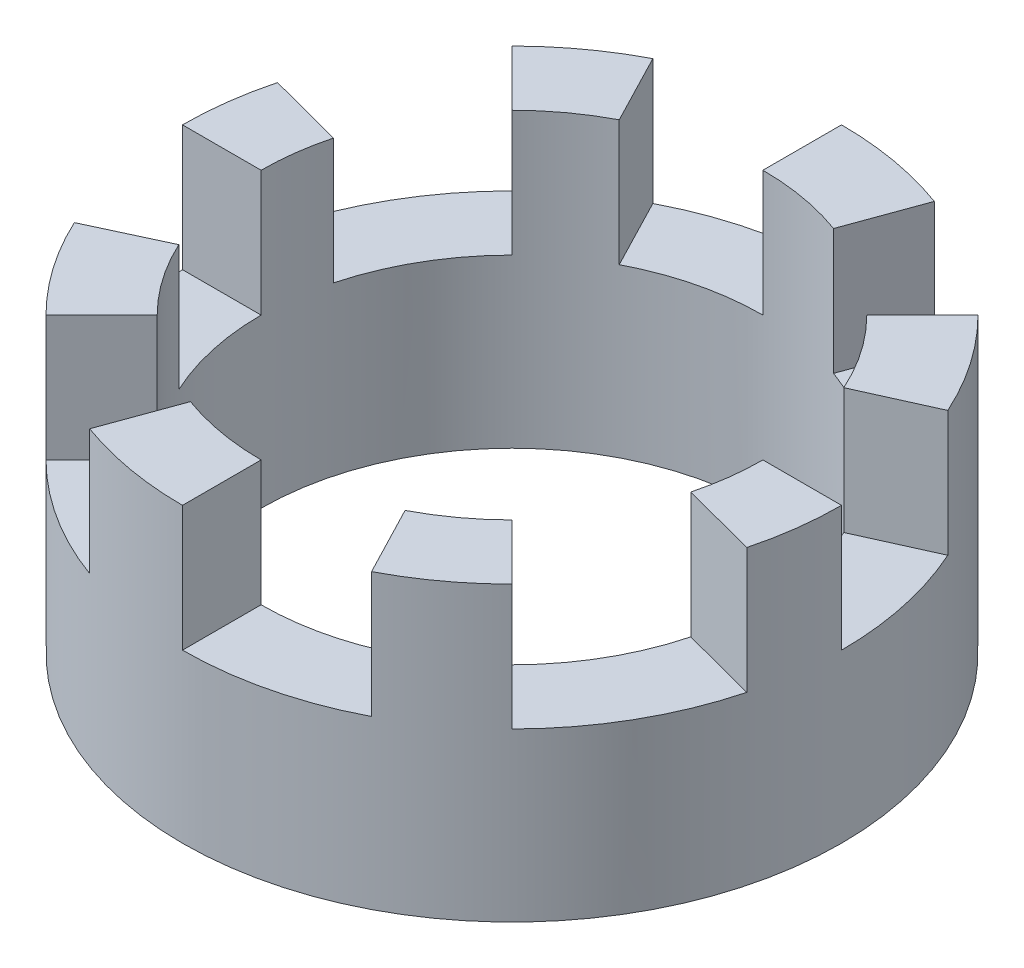
SolidWorks part; units mm, degrees
ref_plane "Front Plane" through (0, 0, 0) normal (0, 0, 1) x (1, 0, 0)
ref_plane "Top Plane" through (0, 0, 0) normal (0, 1, 0) x (1, 0, 0)
ref_plane "Right Plane" through (0, 0, 0) normal (1, 0, 0) x (0, 0, -1)
sketch "Sketch1" plane through (0, 0, 0) normal (0, 1, 0) x (1, 0, 0)
  circle A0 centre (0, 0) radius 30
  circle A1 centre (0, 0) radius 39.4
extrude "Boss-Extrude1" add sketch "Sketch1" along normal blind 20
sketch "Sketch2" plane through (0, 20, 0) normal (0, 1, 0) x (1, 0, 0)
  line L0 (-30, 0) -> (-39.4, 0) construction
  line L1 (-38.0947, 10.0575) -> (-29.0061, 7.658)
  line L2 (30, 0) -> (39.4, 0) construction
  line L3 (38.102, -10.0298) -> (29.0117, -7.6369)
  line L4 (0, 30) -> (0, 39.4) construction
  line L5 (0, -30) -> (0, -39.4) construction
  line L6 (-13.4756, -37.0239) -> (-10.2606, -28.1908)
  line L7 (13.4756, 37.0239) -> (10.2606, 28.1908)
  line L8 (-21.2132, 21.2132) -> (-27.86, 27.86)
  line L9 (-18.1365, 34.9775) -> (-13.8095, 26.6326)
  line L10 (-21.2132, 21.2132) -> (21.2132, -21.2132) construction
  line L11 (21.2132, -21.2132) -> (27.86, -27.86) construction
  line L12 (21.2132, -21.2132) -> (27.86, -27.86)
  line L13 (18.1686, -34.9608) -> (13.834, -26.6199)
  line L14 (-39.4, 0) -> (-30, 0)
  line L15 (0, -30) -> (0, -39.4)
  line L16 (30, 0) -> (39.4, 0)
  line L17 (0, 30) -> (0, 39.4)
  line L18 (-21.2132, -21.2132) -> (-27.86, -27.86)
  line L19 (-27.86, -27.86) -> (21.2132, 21.2132)
  line L20 (21.2132, 21.2132) -> (27.86, 27.86)
  line L21 (-35.7392, -16.5852) -> (-27.2126, -12.6283)
  line L22 (35.9235, 16.1822) -> (27.3529, 12.3215)
  circle A0 centre (0, 0) radius 30 construction
  circle A1 centre (0, 0) radius 39.4 construction
  arc A2 (-39.4, 0) -> (-38.0947, 10.0575) centre (0, 0) cw
  arc A3 (-29.0061, 7.658) -> (-30, 0) centre (0, 0) ccw
  arc A4 (39.4, 0) -> (38.102, -10.0298) centre (0, 0) cw
  arc A5 (30, 0) -> (29.0117, -7.6369) centre (0, 0) cw
  arc A6 (0, -39.4) -> (-13.4756, -37.0239) centre (0, 0) cw
  arc A7 (0, -30) -> (-10.2606, -28.1908) centre (0, 0) cw
  arc A8 (0, 39.4) -> (13.4756, 37.0239) centre (0, 0) cw
  arc A9 (0, 30) -> (10.2606, 28.1908) centre (0, 0) cw
  arc A10 (-30, 0) -> (-21.2132, 21.2132) centre (0, 0) cw
  arc A11 (-27.86, 27.86) -> (-18.1365, 34.9775) centre (0, 0) cw
  arc A12 (-21.2132, 21.2132) -> (-13.8095, 26.6326) centre (0, 0) cw
  arc A13 (27.86, -27.86) -> (18.1686, -34.9608) centre (0, 0) cw
  arc A14 (13.834, -26.6199) -> (21.2132, -21.2132) centre (0, 0) ccw
  arc A15 (-27.86, -27.86) -> (-35.7392, -16.5852) centre (0, 0) cw
  arc A16 (-27.2126, -12.6283) -> (-21.2132, -21.2132) centre (0, 0) ccw
  arc A17 (27.86, 27.86) -> (35.9235, 16.1822) centre (0, 0) cw
  arc A18 (27.3529, 12.3215) -> (21.2132, 21.2132) centre (0, 0) ccw
  circle M5 centre (0, 0) radius 39.4
  circle M6 centre (0, 0) radius 30
extrude "Boss-Extrude2" add sketch "Sketch2" along normal blind 15 contours L14 L1 M5 M6 | L21 L18 M5 M6 | L15 L6 M6 M5 | L13 L12 M5 M6 | L16 L3 M6 M5 | L22 L20 M5 M6 | L17 L7 M6 M5 | L9 L8 M5 M6
